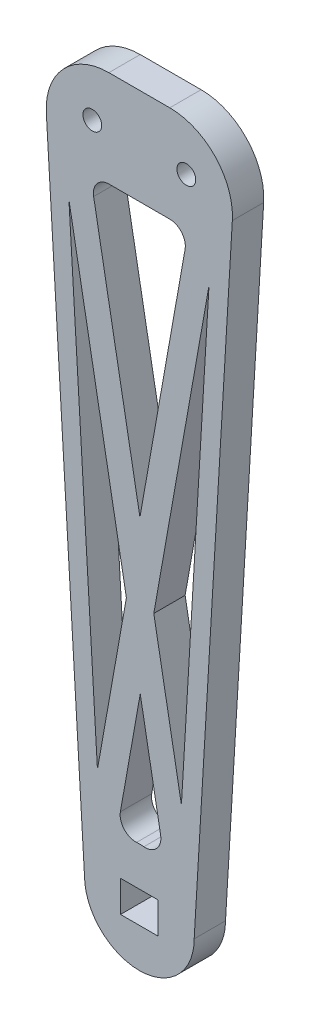
SolidWorks part; units mm, degrees
ref_plane "Front Plane" through (0, 0, 0) normal (0, 0, 1) x (1, 0, 0)
ref_plane "Top Plane" through (0, 0, 0) normal (0, 1, 0) x (1, 0, 0)
ref_plane "Right Plane" through (0, 0, 0) normal (1, 0, 0) x (0, 0, -1)
sketch "Sketch1" plane through (0, 0, 0) normal (0, 0, 1) x (1, 0, 0)
  line L0 (-30, 0) -> (30, 0)
  line L1 (0, 0) -> (15, 0)
  line L2 (55, 0) -> (-55, 0) construction
  line L3 (0, 0) -> (0, -210)
  line L4 (0, -44.7868) -> (0, 44.7868) construction
  line L5 (0, 0) -> (30, 0)
  line L6 (0, 0) -> (-30, 0)
  line L7 (0, 0) -> (-15, 0)
  line L8 (-6, -215) -> (6, -215)
  line L9 (-6, -215) -> (-6, -205)
  line L10 (-6, -205) -> (6, -205)
  line L11 (6, -215) -> (6, -205)
  line L12 (-6, -215) -> (6, -205) construction
  line L13 (-6, -205) -> (6, -215) construction
  line L14 (0, 0) -> (0, 15)
  line L15 (-30, 0) -> (-17.5, -210)
  line L16 (-30, 0) -> (30, 0)
  line L17 (-30, 0) -> (-30, 15.7704)
  line L18 (-30, 15.7704) -> (30, 15.7704)
  line L19 (30, 0) -> (30, 15.7704)
  line L20 (30, 0) -> (17.5, -210)
  circle A0 centre (15, 0) radius 3
  circle A1 centre (-15, 0) radius 3
  circle A2 centre (0, -210) radius 17.5
  point P4 (0, 0)
  dimension "D7" = 6
  dimension "D9" = 6
  dimension "D11" = 35
  dimension "D1" = 210
  dimension "D2" = 30
  dimension "D3" = 30
  dimension "D4" = 10
  dimension "D5" = 12
  dimension "D6" = 15
  dimension "D8" = 15
  dimension "D10" = 15
extrude "Boss-Extrude2" add sketch "Sketch1" along normal blind 10
fillet "Fillet1" radius 20 1 edges at (-30, 15.7704, 5)
fillet "Fillet2" radius 20 1 edges at (30, 15.7704, 5)
sketch "Sketch4" plane through (0, 0, 10) normal (0, 0, 1) x (1, 0, 0)
  line L0 (-29.3398, -11.0918) -> (-23.3398, -11.0918)
  line L1 (-29.6775, -5.418) -> (-17.5, -210) construction
  line L2 (29.3911, -10.23) -> (23.3911, -10.23)
  line L3 (29.6775, -5.418) -> (17.5, -210) construction
  line L4 (-18.3824, -195.1758) -> (-12.3824, -195.1758)
  line L5 (18.3824, -195.1758) -> (12.3824, -195.1758)
  line L6 (-12.3824, -195.1758) -> (-23.5439, -7.6624)
  line L7 (23.3911, -7.6624) -> (11.6198, -205.4193)
  line L8 (-22.9543, -15) -> (22.9543, -15)
  line L9 (-8.4362, -200.1287) -> (-16.4545, -196.0413)
  line L10 (9.2183, -200.015) -> (17.2308, -195.9163)
  line L11 (9.2183, -200.015) -> (-24.5465, -14.245)
  line L12 (17.2308, -195.9163) -> (-16.534, -10.1463)
  line L13 (-24.5465, -14.245) -> (-16.534, -10.1463)
  line L14 (-8.4362, -200.1287) -> (24.4903, -14.4152)
  line L15 (-16.4545, -196.0413) -> (16.472, -10.3277)
  line L16 (24.4903, -14.4152) -> (16.472, -10.3277)
  circle A0 centre (0, -210) radius 17.5
  circle A1 centre (15, 0) radius 15
  point P25 (0, -15)
  dimension "D5" = 15
  dimension "D1" = 6
  dimension "D2" = 6
  dimension "D3" = 6
  dimension "D4" = 6
  dimension "D6" = 9
  dimension "D7" = 9
extrude "Cut-Extrude1" cut sketch "Sketch4" against normal blind 10 contours L12 L15 L8 | L6 L15 L11 | L14 L12 L7 | A0 L11 L14
fillet "Fillet3" radius 5 4 edges at (8.2256, -194.5537, 5) (-7.3724, -194.1287, 5) (-15.6518, -15, 5) (15.6436, -15, 5)
